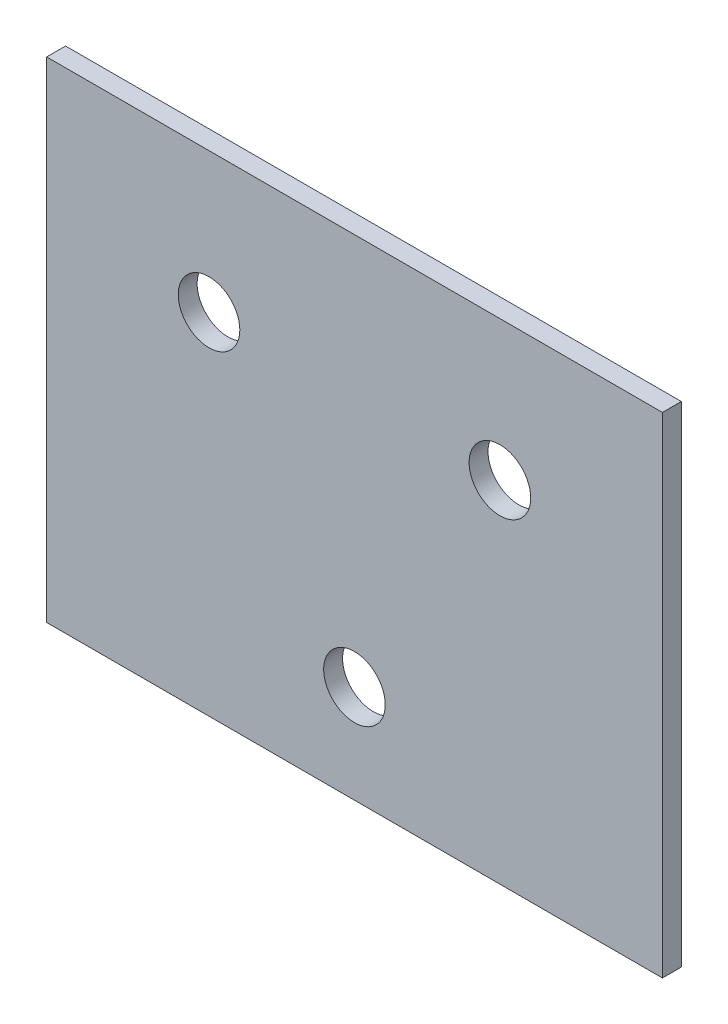
SolidWorks part; units mm, degrees
ref_plane "Front Plane" through (0, 0, 0) normal (0, 0, 1) x (1, 0, 0)
ref_plane "Top Plane" through (0, 0, 0) normal (0, 1, 0) x (1, 0, 0)
ref_plane "Right Plane" through (0, 0, 0) normal (1, 0, 0) x (0, 0, -1)
sketch "Sketch6" plane through (0, 0, 0) normal (0, 0, 1) x (1, 0, 0)
  line L0 (-569.7763, -122.5859) -> (-349.7763, -122.5859)
  line L1 (-349.7763, -122.5859) -> (-349.7763, -297.5859)
  line L2 (-349.7763, -297.5859) -> (-569.7763, -297.5859)
  line L3 (-569.7763, -297.5859) -> (-569.7763, -122.5859)
  circle A0 centre (-459.8079, -202.5859) radius 24
  circle A1 centre (-511.7694, -172.5859) radius 11
  circle A2 centre (-407.8463, -172.5859) radius 11
  circle A3 centre (-459.8079, -262.5859) radius 11
  point P4 (0, 0)
  point P5 (0, 0)
  point P8 (0, 0)
  dimension "D4" = 22
  dimension "D6" = 48
  dimension "D1" = 175
  dimension "D2" = 220
  dimension "D3" = 110.0316
  dimension "D5" = 80
extrude "Boss-Extrude1" add sketch "Sketch6" along normal blind 6.75 contours A0 | L3 L2 L1 L0 A3 A2 A1 A0
